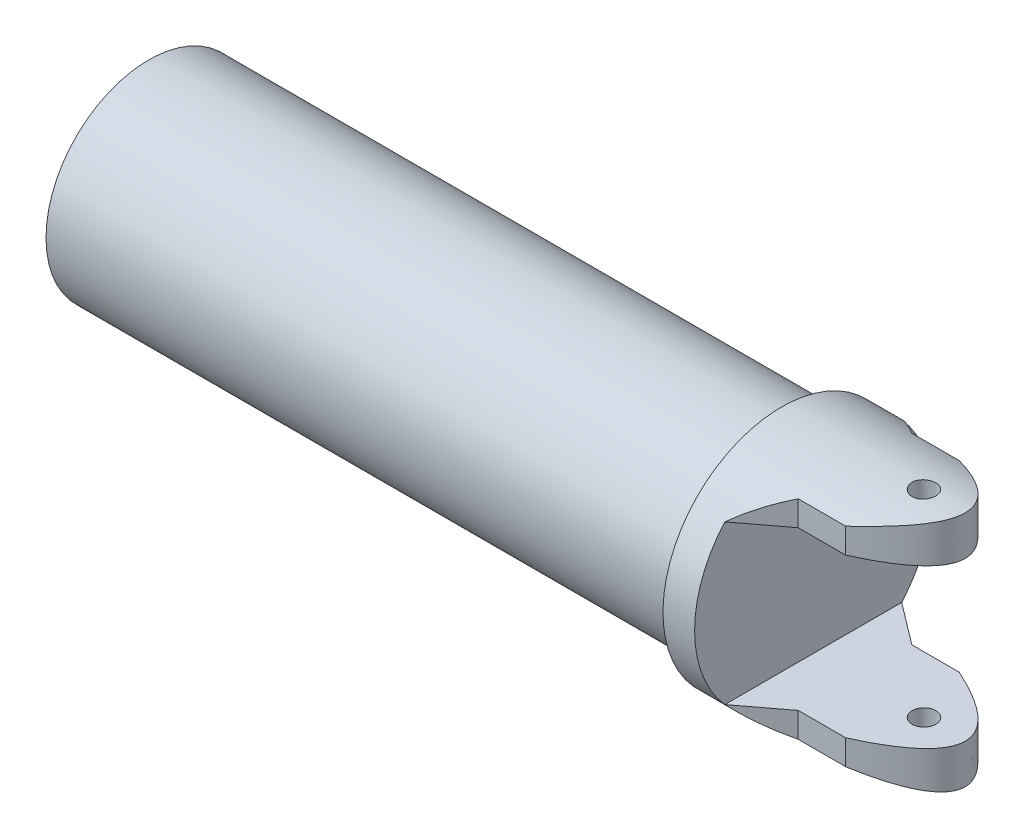
SolidWorks part; units mm, degrees
ref_plane "Front Plane" through (0, 0, 0) normal (0, 0, 1) x (1, 0, 0)
ref_plane "Top Plane" through (0, 0, 0) normal (0, 1, 0) x (1, 0, 0)
ref_plane "Right Plane" through (0, 0, 0) normal (1, 0, 0) x (0, 0, -1)
sketch "Sketch1" plane through (0, 0, 0) normal (1, 0, 0) x (0, 0, -1)
  circle A0 centre (0, 0) radius 6.5
  dimension "D1" = 13
extrude "Boss-Extrude1" add sketch "Sketch1" along normal blind 40
sketch "Sketch2" plane through (40, 0, 0) normal (1, 0, 0) x (0, 0, -1)
  circle A0 centre (0, 0) radius 7.5
  dimension "D1" = 15
extrude "Boss-Extrude2" add sketch "Sketch2" along normal blind 2
sketch "Sketch3" plane through (42, 0, 0) normal (1, 0, 0) x (0, 0, -1)
  line L1 (-5.5902, -5) -> (5.5902, -5)
  line L2 (-5.5902, -5) -> (-5.5902, 5)
  line L3 (-5.5902, 5) -> (5.5902, 5)
  line L4 (5.5902, -5) -> (5.5902, 5)
  line L5 (-5.5902, -5) -> (5.5902, 5) construction
  line L6 (-5.5902, 5) -> (5.5902, -5) construction
  arc A0 (-4.899, 5) -> (-4.899, -5) centre (0, 0) ccw
  circle A1 centre (0, 0) radius 7.5 construction
  arc A2 (4.899, -5) -> (4.899, 5) centre (0, 0) ccw
  point P0 (0, 0)
  circle M2 centre (0, 0) radius 7.5
  dimension "D1" = 10
extrude "Boss-Extrude3" add sketch "Sketch3" along normal blind 10 contours L3 M2 | L1 M2
sketch "Sketch4" plane through (0, 5, 0) normal (0, -1, 0) x (1, 0, 0)
  line L0 (52, 0) -> (5.8747, 0) construction
  line L1 (52, 5.5902) -> (52, -5.5902) construction
  line L7 (42, 5.5902) -> (52, 5.5902)
  line L8 (52, 5.5902) -> (52, -5.5902)
  line L9 (52, -5.5902) -> (42, -5.5902)
  line L10 (42, 5.5902) -> (44.6404, 3.5902)
  line L11 (44.6404, 3.5902) -> (47.6404, 3.5902)
  line L12 (47.6404, -3.5902) -> (44.6404, -3.5902)
  line L13 (44.6404, -3.5902) -> (42, -5.5902)
  spline S0 degree 3 poles (47.6404, -3.5902) (50.2801, -2.3934) (52.9199, 0) (50.2801, 2.3934) (47.6404, 3.5902) knots 0.178885 0.178885 0.178885 0.178885 0.5 0.821115 0.821115 0.821115 0.821115
  dimension "D1" = 9.6
  dimension "D2" = 3
  dimension "D3" = 2
  dimension "D4" = 3
  dimension "D5" = 2
extrude "Cut-Extrude1" cut sketch "Sketch4" against normal through all both and the other way through all
sketch "Sketch5" plane through (0, 5, 0) normal (0, -1, 0) x (1, 0, 0)
  line L0 (42, 0) -> (17.8474, 0) construction
  line L1 (42, 5.5902) -> (42, -5.5902) construction
  circle A0 centre (49, 0) radius 0.75
  dimension "D2" = 1.5
  dimension "D1" = 7
extrude "Cut-Extrude2" cut sketch "Sketch5" against normal through all both and the other way through all
sketch "Sketch6" plane through (0, 0, 0) normal (-1, 0, 0) x (0, 0, 1)
  line L0 (0, 5) -> (0, -5) construction
  line L1 (-5, 0) -> (5, 0) construction
  line L3 (4, -0.5) -> (4.9749, -0.5)
  line L4 (4, -0.5) -> (4, 0.5)
  line L5 (4, 0.5) -> (4.9749, 0.5)
  line L7 (4, -0.5) -> (6, 0.5) construction
  line L8 (4, 0.5) -> (6, -0.5) construction
  line L9 (-0.5, 4) -> (0.5, 4)
  line L10 (-0.5, 4) -> (-0.5, 4.9749)
  line L12 (0.5, 4) -> (0.5, 4.9749)
  line L13 (-0.5, 4) -> (0.5, 6) construction
  line L14 (-0.5, 6) -> (0.5, 4) construction
  line L15 (-4, -0.5) -> (-4.9749, -0.5)
  line L16 (-4, -0.5) -> (-4, 0.5)
  line L17 (-4, 0.5) -> (-4.9749, 0.5)
  line L19 (-4, -0.5) -> (-6, 0.5) construction
  line L20 (-4, 0.5) -> (-6, -0.5) construction
  line L21 (-0.5, -4) -> (0.5, -4)
  line L22 (-0.5, -4) -> (-0.5, -4.9749)
  line L24 (0.5, -4) -> (0.5, -4.9749)
  line L25 (-0.5, -4) -> (0.5, -6) construction
  line L26 (-0.5, -6) -> (0.5, -4) construction
  arc A0 (-0.5, 4.9749) -> (-4.9749, 0.5) centre (0, 0) ccw
  arc A1 (4.9749, 0.5) -> (0.5, 4.9749) centre (0, 0) ccw
  arc A2 (0.5, -4.9749) -> (4.9749, -0.5) centre (0, 0) ccw
  arc A3 (-4.9749, -0.5) -> (-0.5, -4.9749) centre (0, 0) ccw
  dimension "D1" = 10
  dimension "D2" = 1
  dimension "D3" = 2
  dimension "D4" = 2
  dimension "D5" = 1
  dimension "D6" = 2
  dimension "D7" = 1
  dimension "D8" = 1
  dimension "D9" = 2
extrude "Cut-Extrude3" cut sketch "Sketch6" against normal blind 30
